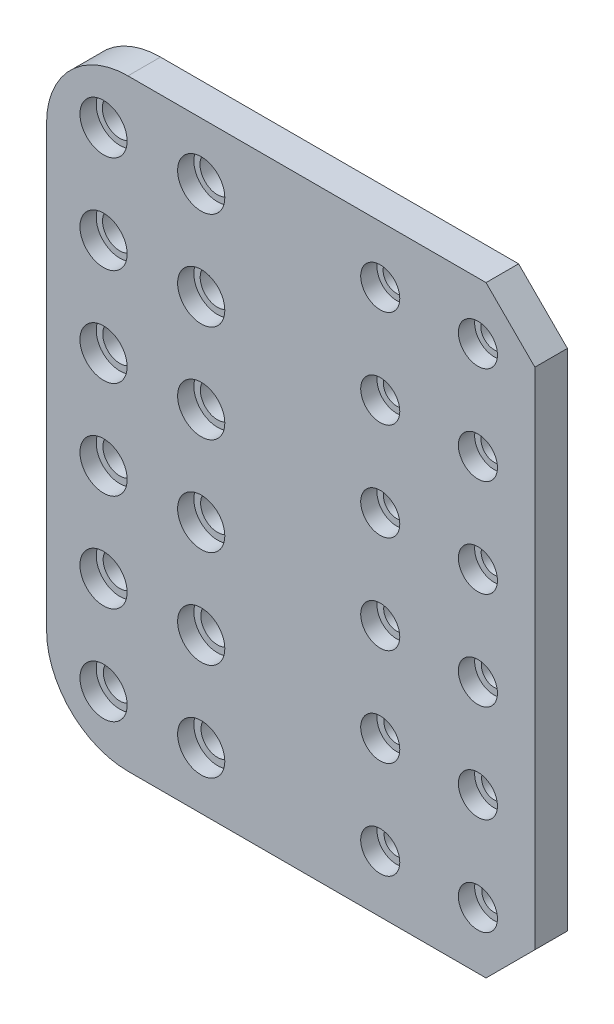
SolidWorks part; units mm, degrees
ref_plane "Front Plane" through (0, 0, 0) normal (0, 0, 1) x (1, 0, 0)
ref_plane "Top Plane" through (0, 0, 0) normal (0, 1, 0) x (1, 0, 0)
ref_plane "Right Plane" through (0, 0, 0) normal (1, 0, 0) x (0, 0, -1)
sketch "Sketch1" plane through (0, 0, 0) normal (0, 0, 1) x (1, 0, 0)
  line L1 (30, 37) -> (-30, 37)
  line L2 (30, 37) -> (30, -37)
  line L3 (30, -37) -> (-30, -37)
  line L4 (-30, 37) -> (-30, -37)
  line L5 (30, 37) -> (-30, -37) construction
  line L6 (30, -37) -> (-30, 37) construction
  point P0 (0, 0)
  dimension "D1" = 60
  dimension "D2" = 74
extrude "Boss-Extrude1" add sketch "Sketch1" along normal blind 12
sketch "Sketch3" plane through (0, 0, 12) normal (0, 0, 1) x (1, 0, 0)
  line L0 (-30, -37) -> (-23, -37) construction
  line L1 (-30, -37) -> (30, -37) construction
  line L2 (-23, -37) -> (-23, -30) construction
  line L3 (30, -37) -> (23, -37) construction
  line L4 (23, -37) -> (23, -30) construction
  circle A0 centre (-23, -30) radius 1.65
  circle A1 centre (23, -30) radius 1.15
  circle A2 centre (-11, -30) radius 1.65
  circle A3 centre (-11, -18) radius 1.65
  circle A4 centre (-11, -6) radius 1.65
  circle A5 centre (-11, 6) radius 1.65
  circle A6 centre (-23, -18) radius 1.65
  circle A7 centre (-23, -6) radius 1.65
  circle A8 centre (-23, 6) radius 1.65
  circle A9 centre (11, -30) radius 1.15
  circle A10 centre (11, -18) radius 1.15
  circle A11 centre (11, -6) radius 1.15
  circle A12 centre (11, 6) radius 1.15
  circle A13 centre (23, -18) radius 1.15
  circle A14 centre (23, -6) radius 1.15
  circle A15 centre (23, 6) radius 1.15
  circle A16 centre (-23, 18) radius 1.65
  circle A17 centre (-11, 18) radius 1.65
  circle A18 centre (-23, 30) radius 1.65
  circle A19 centre (-11, 30) radius 1.65
  circle A20 centre (23, 18) radius 1.15
  circle A21 centre (11, 18) radius 1.15
  circle A22 centre (23, 30) radius 1.15
  circle A23 centre (11, 30) radius 1.15
  dimension "D2" = 3.3
  dimension "D3" = 2.3
  dimension "D1" = 7
  dimension "D6" = 12
  dimension "D7" = 12
  dimension "D4" = 2
  dimension "D5" = 6
  dimension "D8" = 2
  dimension "D9" = 6
extrude "Cut-Extrude1" cut sketch "Sketch3" against normal through all
sketch "Sketch4" plane through (0, 0, 12) normal (0, 0, 1) x (1, 0, 0)
  circle A1 centre (-23, -30) radius 2.9
  circle A3 centre (-11, -30) radius 2.9
  circle A4 centre (-11, -18) radius 2.9
  circle A5 centre (-11, -6) radius 2.9
  circle A6 centre (-11, 6) radius 2.9
  circle A7 centre (-23, -18) radius 2.9
  circle A8 centre (-23, -6) radius 2.9
  circle A9 centre (-23, 6) radius 2.9
  circle A10 centre (11, -30) radius 2.4
  circle A11 centre (23, -30) radius 2.4
  circle A12 centre (23, -18) radius 2.4
  circle A13 centre (23, -6) radius 2.4
  circle A14 centre (23, 6) radius 2.4
  circle A15 centre (11, -18) radius 2.4
  circle A16 centre (11, -6) radius 2.4
  circle A17 centre (11, 6) radius 2.4
  circle A18 centre (-23, 18) radius 2.9
  circle A19 centre (-11, 18) radius 2.9
  circle A20 centre (-23, 30) radius 2.9
  circle A21 centre (-11, 30) radius 2.9
  circle A22 centre (11, 18) radius 2.4
  circle A23 centre (23, 18) radius 2.4
  circle A24 centre (11, 30) radius 2.4
  circle A25 centre (23, 30) radius 2.4
  dimension "D1" = 5.8
  dimension "D4" = 4.8
  dimension "D2" = 2
  dimension "D3" = 6
  dimension "D5" = 2
  dimension "D6" = 6
chamfer "Chamfer1" distance 6 angle 45 2 edges at (30, 37, 6) (30, -37, 6)
fillet "Fillet1" radius 10 2 edges at (-30, -37, 6) (-30, 37, 6)
extrude "Cut-Extrude2" cut sketch "Sketch4" against normal blind 2
sketch "Sketch6" plane through (0, 0, 10) normal (0, 0, 1) x (1, 0, 0)
  circle A0 centre (-23, 30) radius 2.15
  circle A1 centre (-23, 18) radius 2.125
  circle A2 centre (-23, 6) radius 2.1
  circle A3 centre (-23, -6) radius 2.075
  circle A4 centre (-23, -18) radius 2.05
  circle A5 centre (-23, -30) radius 2.025
  circle A6 centre (-11, 30) radius 2.15
  circle A7 centre (11, -30) radius 1.525
  circle A8 centre (11, -18) radius 1.55
  circle A9 centre (11, -6) radius 1.575
  circle A10 centre (11, 6) radius 1.6
  circle A11 centre (11, 18) radius 1.625
  circle A12 centre (11, 30) radius 1.65
  circle A13 centre (-11, 18) radius 2.125
  circle A14 centre (-11, 6) radius 2.1
  circle A15 centre (-11, -6) radius 2.075
  circle A16 centre (-11, -18) radius 2.05
  circle A17 centre (-11, -30) radius 2.025
  circle A18 centre (23, -30) radius 1.525
  circle A19 centre (23, -18) radius 1.55
  circle A20 centre (23, -6) radius 1.575
  circle A21 centre (23, 6) radius 1.6
  circle A22 centre (23, 18) radius 1.625
  circle A23 centre (23, 30) radius 1.65
  dimension "D1" = 4.05
  dimension "D2" = 4.1
  dimension "D3" = 4.15
  dimension "D4" = 4.2
  dimension "D5" = 4.25
  dimension "D6" = 4.3
  dimension "D7" = 3.3
  dimension "D8" = 3.25
  dimension "D9" = 3.2
  dimension "D10" = 3.15
  dimension "D11" = 3.1
  dimension "D12" = 3.05
  dimension "D13" = 2
  dimension "D14" = 2
extrude "Cut-Extrude3" cut sketch "Sketch6" against normal blind 3.1
sketch "Sketch8" plane through (-30, 0, 0) normal (-1, 0, 0) x (0, 0, 1)
  line L5 (12, -37) -> (0, -37) construction
  line L6 (0, 37) -> (8, 37)
  line L7 (0, 37) -> (0, -37)
  line L8 (0, -37) -> (8, -37)
  line L9 (8, 37) -> (8, -37)
  line L10 (0, 37) -> (8, -37) construction
  line L11 (0, -37) -> (8, 37) construction
  point P4 (4, 0)
  dimension "D1" = 4
extrude "Cut-Extrude4" cut sketch "Sketch8" against normal through all
